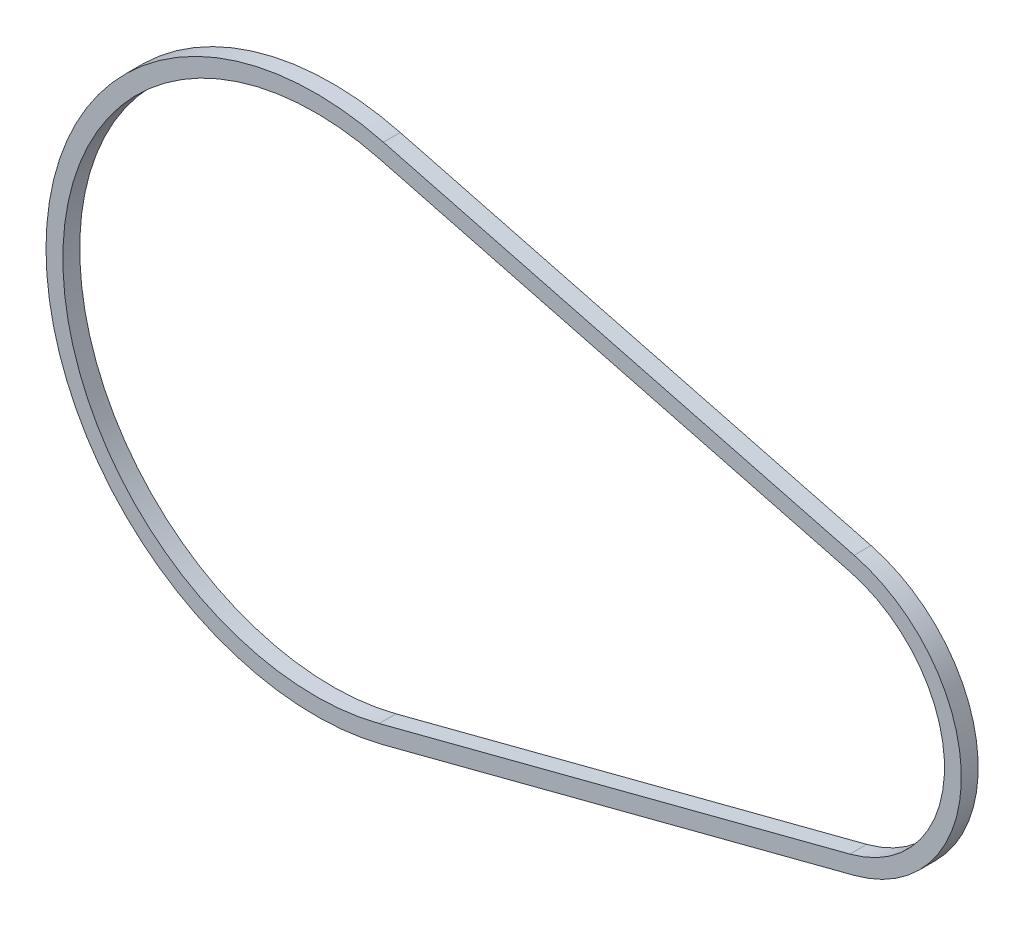
SolidWorks part; units mm, degrees
material "BUTYL"
ref_plane "Front Plane" through (0, 0, 0) normal (0, 0, 1) x (1, 0, 0)
ref_plane "Top Plane" through (0, 0, 0) normal (0, 1, 0) x (1, 0, 0)
ref_plane "Right Plane" through (0, 0, 0) normal (1, 0, 0) x (0, 0, -1)
sketch "Sketch1" plane through (0, 0, 0) normal (0, 0, 1) x (1, 0, 0)
  line L0 (0, 0) -> (298.24, 0) construction
  line L1 (37.7213, 145.1796) -> (317.1006, 72.5898)
  line L2 (37.7213, -145.1796) -> (317.1006, -72.5898)
  line L3 (40.2361, 154.8582) -> (319.6154, 82.2684)
  line L4 (40.2361, -154.8582) -> (319.6154, -82.2684)
  arc A0 (37.7213, 145.1796) -> (37.7213, -145.1796) centre (0, 0) ccw
  arc A1 (317.1006, -72.5898) -> (317.1006, 72.5898) centre (298.24, 0) ccw
  arc A2 (319.6154, -82.2684) -> (319.6154, 82.2684) centre (298.24, 0) ccw
  arc A3 (40.2361, 154.8582) -> (40.2361, -154.8582) centre (0, 0) ccw
  dimension "D1" = 298.24
  dimension "D2" = 10
extrude "Boss-Extrude1" add sketch "Sketch1" along normal blind 10
